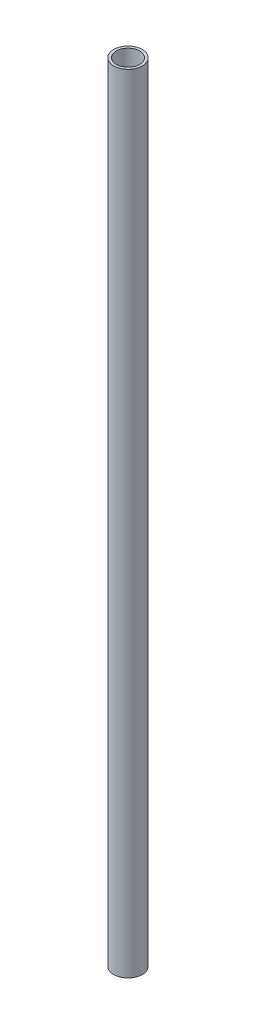
SolidWorks part; units mm, degrees
ref_plane "Front Plane" through (0, 0, 0) normal (0, 0, 1) x (1, 0, 0)
ref_plane "Top Plane" through (0, 0, 0) normal (0, 1, 0) x (1, 0, 0)
ref_plane "Right Plane" through (0, 0, 0) normal (1, 0, 0) x (0, 0, -1)
sketch "Sketch1" plane through (0, 0, 0) normal (0, 1, 0) x (1, 0, 0)
  circle A0 centre (0, 0) radius 21.082
  circle A1 centre (0, 0) radius 17.272
  dimension "D1" = 34.544
  dimension "1.66" = 42.164
extrude "Boss-Extrude1" add sketch "Sketch1" along normal blind 1160.4625
ref_plane "Plane1" through (0, 0, 21.082) normal (0, 0, 1) x (1, 0, 0)
sketch "Sketch2" plane through (0, 0, 21.082) normal (0, 0, 1) x (1, 0, 0)
  line L0 (-21.082, 1.5875) -> (21.082, 1.5875) construction
  line L1 (-21.082, 1160.4625) -> (-21.082, 0) construction
  line L2 (-21.082, 0) -> (21.082, 0) construction
  line L3 (-21.082, 103.1875) -> (21.082, 103.1875) construction
  line L4 (21.082, 0) -> (21.082, 1160.4625) construction
  point P0 (0, 25.4)
  point P1 (0, 92.075)
  dimension "D1" = 1.5875
  dimension "D2" = 66.675
  dimension "D3" = 25.4
  dimension "D4" = 101.6
hole_wizard "1/4 Clearance Hole1" positions "Sketch3" profile "Sketch4" hole size "1/4" standard "ANSI Inch"
sketch "Sketch3" plane through (0, 0, 21.082) normal (0, 0, 1) x (1, 0, 0)
  point P0 (0, 25.4)
  point P3 (0, 92.075)
sketch "Sketch4" plane through (0, 25.4, 21.082) normal (1, 0, 0) x (0, -1, 0)
  line L0 (0, 0) -> (0, 42.164)
  line L1 (0, 42.164) -> (3.3782, 42.164)
  line L2 (3.3782, 42.164) -> (3.3782, 0)
  line L5 (3.3782, 0) -> (0, 0)
  line L11 (0, -6.35) -> (0, 107.95) construction
  dimension "Thru Hole Dia." = 6.7564
  dimension "Thru Hole Depth" = 42.164
